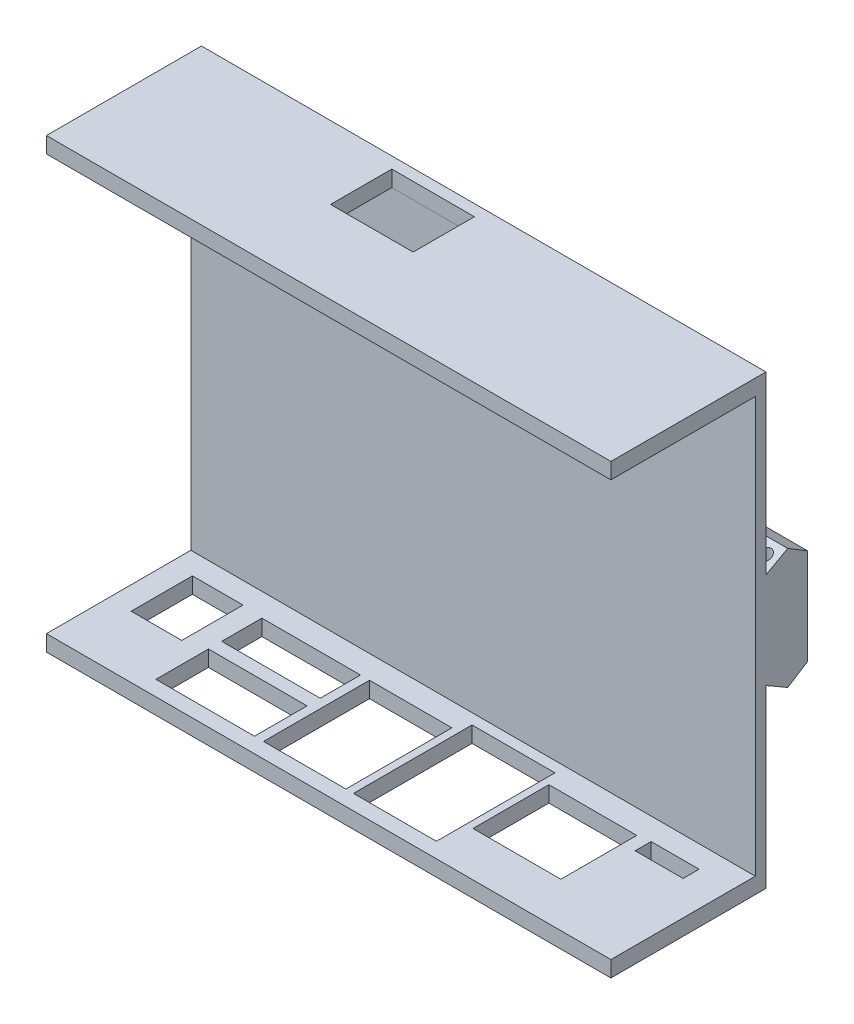
SolidWorks part; units mm, degrees
ref_plane "Front Plane" through (0, 0, 0) normal (0, 0, 1) x (1, 0, 0)
ref_plane "Top Plane" through (0, 0, 0) normal (0, 1, 0) x (1, 0, 0)
ref_plane "Right Plane" through (0, 0, 0) normal (1, 0, 0) x (0, 0, -1)
other "Graphic1"
other "Graphic (Closed) -1"
sketch "Sketch1" plane through (0, 0, 0) normal (0, 1, 0) x (1, 0, 0)
  line L1 (72.067, 0.1397) -> (178.0588, 0.1397)
  line L2 (72.067, 0.1397) -> (72.067, -28.9703)
  line L3 (72.067, -28.9703) -> (178.0588, -28.9703)
  line L4 (178.0588, 0.1397) -> (178.0588, -28.9703)
  line L5 (76.3779, -17.367) -> (85.8779, -17.367)
  line L6 (76.3779, -17.367) -> (76.3779, -5.8674)
  line L7 (76.3779, -5.8674) -> (85.8779, -5.8674)
  line L8 (85.8779, -17.367) -> (85.8779, -5.8674)
  line L9 (89.7779, -26.117) -> (108.2779, -26.117)
  line L10 (89.7779, -26.117) -> (89.7779, -16.248)
  line L11 (89.7779, -16.248) -> (108.2779, -16.248)
  line L12 (108.2779, -26.117) -> (108.2779, -16.248)
  line L13 (89.7779, -6.217) -> (108.2779, -6.217)
  line L14 (89.7779, -6.217) -> (89.7779, -13.7671)
  line L15 (89.7779, -13.7671) -> (108.2779, -13.7671)
  line L16 (108.2779, -6.217) -> (108.2779, -13.7671)
  line L17 (109.9779, -26.117) -> (125.45, -26.117)
  line L18 (109.9779, -26.117) -> (109.9779, -6.217)
  line L19 (109.9779, -6.217) -> (125.45, -6.217)
  line L20 (125.45, -26.117) -> (125.45, -6.217)
  line L21 (126.875, -26.117) -> (142.45, -26.117)
  line L22 (126.875, -26.117) -> (126.875, -3.8603)
  line L23 (126.875, -3.8603) -> (142.45, -3.8603)
  line L24 (142.45, -26.117) -> (142.45, -3.8603)
  line L25 (143.8, -20.6066) -> (160.3, -20.6066)
  line L26 (143.8, -20.6066) -> (143.8, -6.3566)
  line L27 (143.8, -6.3566) -> (160.3, -6.3566)
  line L28 (160.3, -20.6066) -> (160.3, -6.3566)
  line L29 (162.65, -9.007) -> (171.65, -9.007)
  line L30 (162.65, -9.007) -> (162.65, -6.007)
  line L31 (162.65, -6.007) -> (171.65, -6.007)
  line L32 (171.65, -9.007) -> (171.65, -6.007)
  point P4 (0, 0)
  point P9 (0, 0)
  point P10 (0, 0)
  point P15 (0, 0)
  point P46 (0, 0)
  point P47 (0, 0)
  point P48 (0, 0)
  point P49 (0, 0)
  dimension "D1" = 4.3109
  dimension "D2" = 6.007
  dimension "D3" = 11.6033
  dimension "D4" = 13.8109
  dimension "D5" = 17.7109
  dimension "D6" = 6.3566
  dimension "D7" = 2.4809
  dimension "D8" = 36.2109
  dimension "D9" = 29.1099
  dimension "D10" = 105.9917
  dimension "D11" = 1.7
  dimension "D12" = 2.8533
  dimension "D13" = 2.3566
  dimension "D14" = 18.5
  dimension "D15" = 7.5501
  dimension "D16" = 15.4721
  dimension "D17" = 1.35
  dimension "D18" = 2.4963
  dimension "D19" = 5.5103
  dimension "D20" = 16.5
  dimension "D21" = 2.35
  dimension "D22" = 6.1467
  dimension "D23" = 6.4088
  dimension "D24" = 9
  dimension "D25" = 3
extrude "Boss-Extrude1" add sketch "Sketch1" along normal blind 84 contours L1 L4 L3 L2
sketch "Sketch3" plane through (0, 84, 0) normal (0, 1, 0) x (1, 0, 0)
  line L0 (72.067, 0.1397) -> (178.0588, 0.1397) construction
  line L1 (109.95, -2) -> (125.45, -2)
  line L2 (109.95, -2) -> (109.95, -13.5)
  line L3 (109.95, -13.5) -> (125.45, -13.5)
  line L4 (125.45, -2) -> (125.45, -13.5)
  line L5 (72.067, 0.1397) -> (72.067, -28.9703) construction
  dimension "D1" = 11.5
  dimension "D2" = 15.5
  dimension "D3" = 2.1397
  dimension "D4" = 37.883
sketch "Sketch4" plane through (72.067, 0, 0) normal (-1, 0, 0) x (0, 0, 1)
  line L0 (28.9703, 84) -> (28.9703, 0) construction
  line L1 (28.9703, 81) -> (1.8603, 81)
  line L2 (28.9703, 81) -> (28.9703, 3)
  line L3 (28.9703, 3) -> (1.8603, 3)
  line L4 (1.8603, 81) -> (1.8603, 3)
  line L5 (-0.1397, 84) -> (28.9703, 84) construction
  line L6 (-0.1397, 0) -> (28.9703, 0) construction
  line L7 (-0.1397, 84) -> (-0.1397, 0) construction
  dimension "D1" = 3
  dimension "D2" = 3
  dimension "D3" = 2
extrude "Cut-Extrude1" cut sketch "Sketch3" against normal blind 3 and the other way through all
extrude "Cut-Extrude2" cut sketch "Sketch4" against normal through all and the other way through all
sketch "Sketch5" plane through (0, 0, 0) normal (0, -1, 0) x (1, 0, 0)
  line L1 (76.3779, 17.367) -> (85.8779, 17.367)
  line L2 (76.3779, 17.367) -> (76.3779, 5.8674)
  line L3 (76.3779, 5.8674) -> (85.8779, 5.8674)
  line L4 (85.8779, 17.367) -> (85.8779, 5.8674)
  line L5 (89.7779, 26.117) -> (108.2779, 26.117)
  line L6 (89.7779, 26.117) -> (89.7779, 16.248)
  line L7 (89.7779, 16.248) -> (108.2779, 16.248)
  line L8 (108.2779, 26.117) -> (108.2779, 16.248)
  line L9 (89.7779, 13.7671) -> (108.2779, 13.7671)
  line L10 (89.7779, 13.7671) -> (89.7779, 6.217)
  line L11 (89.7779, 6.217) -> (108.2779, 6.217)
  line L12 (108.2779, 13.7671) -> (108.2779, 6.217)
  line L13 (109.9779, 26.117) -> (125.45, 26.117)
  line L14 (109.9779, 26.117) -> (109.9779, 6.217)
  line L15 (109.9779, 6.217) -> (125.45, 6.217)
  line L16 (125.45, 26.117) -> (125.45, 6.217)
  line L17 (126.875, 26.117) -> (142.45, 26.117)
  line L18 (126.875, 26.117) -> (126.875, 3.8603)
  line L19 (126.875, 3.8603) -> (142.45, 3.8603)
  line L20 (142.45, 26.117) -> (142.45, 3.8603)
  line L21 (143.8, 20.6066) -> (160.3, 20.6066)
  line L22 (143.8, 20.6066) -> (143.8, 6.3566)
  line L23 (143.8, 6.3566) -> (160.3, 6.3566)
  line L24 (160.3, 20.6066) -> (160.3, 6.3566)
  line L25 (162.65, 9.007) -> (171.65, 9.007)
  line L26 (162.65, 9.007) -> (162.65, 6.007)
  line L27 (162.65, 6.007) -> (171.65, 6.007)
  line L28 (171.65, 9.007) -> (171.65, 6.007)
extrude "Cut-Extrude3" cut sketch "Sketch5" against normal blind 3
sketch "Sketch6" plane through (72.067, 0, 0) normal (-1, 0, 0) x (0, 0, 1)
  line L0 (-0.1397, 33) -> (-0.1397, 51)
  line L1 (-0.1397, 51) -> (-4.2296, 53.2541)
  line L2 (-4.2296, 53.2541) -> (-7.9606, 51)
  line L3 (-7.9606, 51) -> (-7.9606, 33)
  line L4 (-7.9606, 33) -> (-4.2296, 30.6387)
  line L5 (-4.2296, 30.6387) -> (-0.1397, 33)
  line L6 (-0.1397, 84) -> (-0.1397, 0) construction
  point P3 (0, 0)
  point P7 (0, 0)
  point P8 (0, 0)
  point P11 (-0.1397, 42)
  dimension "D1" = 120
  dimension "D2" = 18
  dimension "D3" = 120
  dimension "D4" = 4.67
  dimension "D5" = 4.3591
extrude "Boss-Extrude2" add sketch "Sketch6" against normal up to surface (105.9917 mm away) contours L3 L4 L5 L0 L1 L2 up to face at (178.0588, 42, 14.9153)
sketch "Sketch7" plane through (0, 0, 0) normal (0, 1, 0) x (1, 0, 0)
  line L0 (72.067, 0.1397) -> (72.067, 4.2296) construction
  line L1 (72.067, 0.1397) -> (178.0588, 0.1397) construction
  circle A0 centre (75.777, 2.2397) radius 1
  dimension "D1" = 2
  dimension "D2" = 3.71
  dimension "D3" = 2.1
extrude "Cut-Extrude4" cut sketch "Sketch7" along normal through all and the other way through all
pattern_linear "LPattern1" count 28 spacing 3.71 along (1, 0, 0) of "Cut-Extrude4"
